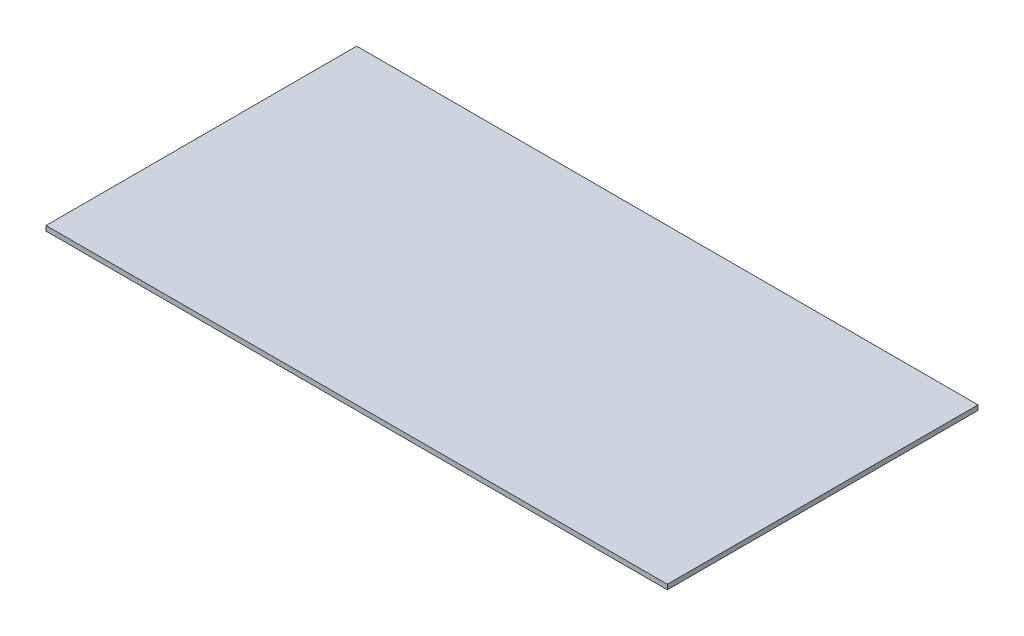
SolidWorks part; units mm, degrees
ref_plane "Front Plane" through (0, 0, 0) normal (0, 0, 1) x (1, 0, 0)
ref_plane "Top Plane" through (0, 0, 0) normal (0, 1, 0) x (1, 0, 0)
ref_plane "Right Plane" through (0, 0, 0) normal (1, 0, 0) x (0, 0, -1)
sketch "Sketch1" plane through (0, 0, 0) normal (0, 1, 0) x (1, 0, 0)
  line L1 (0, 0) -> (2438.4, 0)
  line L2 (0, 0) -> (0, 1219.2)
  line L3 (0, 1219.2) -> (2438.4, 1219.2)
  line L4 (2438.4, 0) -> (2438.4, 1219.2)
extrude "Boss-Extrude1" add sketch "Sketch1" along normal blind 19.05
